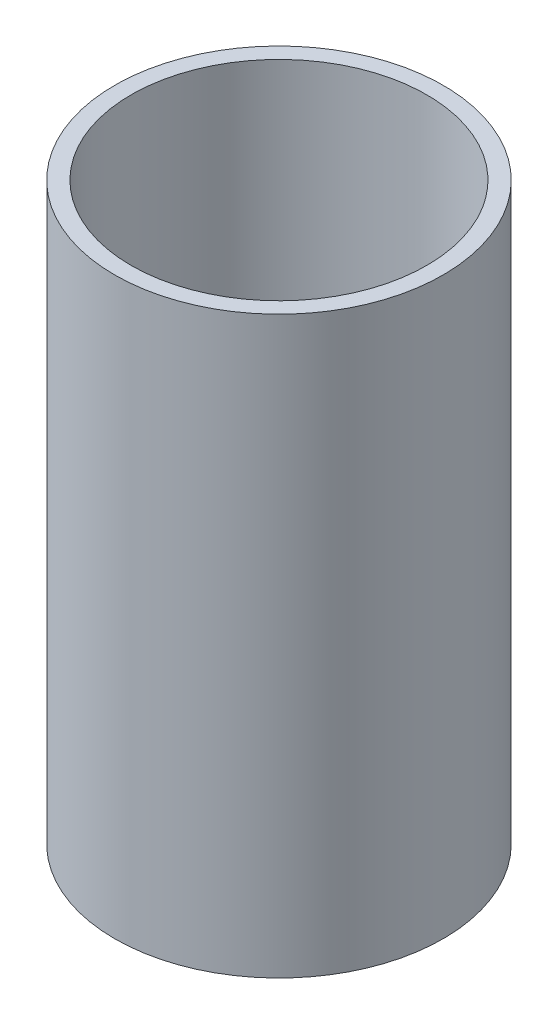
SolidWorks part; units mm, degrees
ref_plane "前视基准面" through (0, 0, 0) normal (0, 0, 1) x (1, 0, 0)
ref_plane "上视基准面" through (0, 0, 0) normal (0, 1, 0) x (1, 0, 0)
ref_plane "右视基准面" through (0, 0, 0) normal (1, 0, 0) x (0, 0, -1)
other "Configuration Table"
sketch "草图1" plane through (0, 0, 0) normal (0, 1, 0) x (1, 0, 0)
  circle A0 centre (0, 0) radius 20
  circle A1 centre (0, 0) radius 18
  dimension "D1" = 40
  dimension "D2" = 36
extrude "凸台-拉伸1" add sketch "草图1" along normal blind 70
